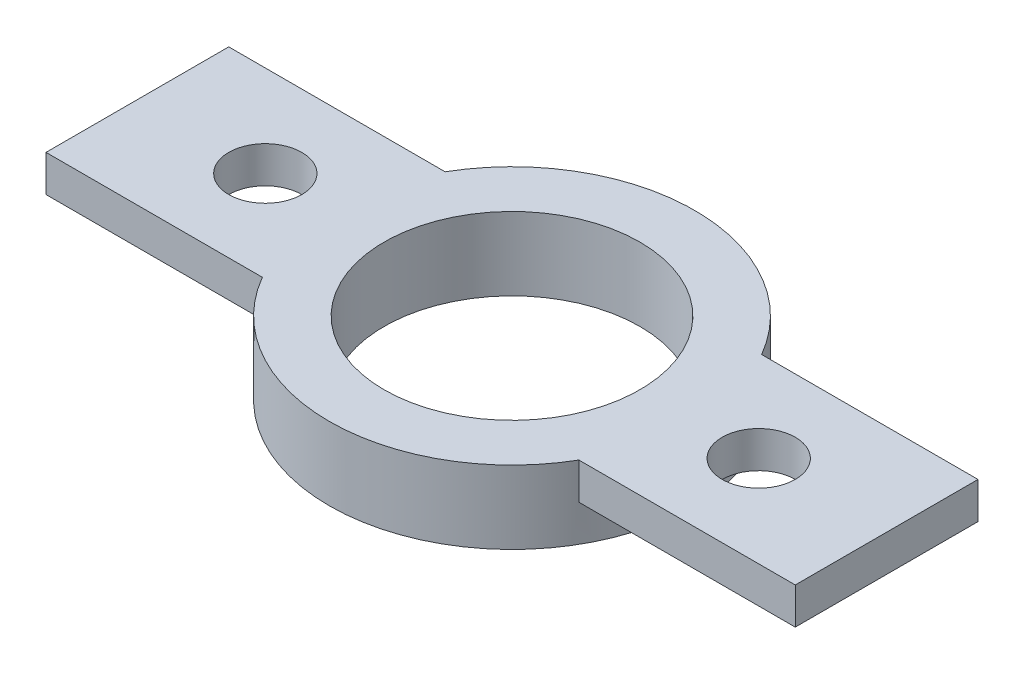
SolidWorks part; units mm, degrees
ref_plane "Front" through (0, 0, 0) normal (0, 0, 1) x (1, 0, 0)
ref_plane "Top" through (0, 0, 0) normal (0, 1, 0) x (1, 0, 0)
ref_plane "Right" through (0, 0, 0) normal (1, 0, 0) x (0, 0, -1)
sketch "Sketch1" plane through (0, 0, 0) normal (0, 1, 0) x (1, 0, 0)
  line L1 (0, 0) -> (35, 0)
  line L2 (0, 0) -> (0, 10)
  line L3 (0, 10) -> (35, 10)
  line L4 (35, 0) -> (35, 10)
  dimension "D1" = 35
  dimension "D2" = 10
extrude "Boss-Extrude1" add sketch "Sketch1" along normal blind 2
sketch "Sketch2" plane through (0, 2, 0) normal (0, 1, 0) x (1, 0, 0)
  line L0 (0, 10) -> (0, 0) construction
  line L2 (0, 0) -> (35, 0) construction
  circle A0 centre (17.5, 5) radius 10
  point P6 (22.496, 10.5283)
  dimension "D1" = 17.5
  dimension "D2" = 5
extrude "Boss-Extrude2" add sketch "Sketch2" against normal blind 4
sketch "Sketch3" plane through (0, 2, 0) normal (0, 1, 0) x (1, 0, 0)
  circle A0 centre (17.5, 5) radius 7
extrude "Cut-Extrude1" cut sketch "Sketch3" against normal blind 2000
sketch "Sketch4" plane through (0, 0, 0) normal (0, -1, 0) x (1, 0, 0)
  line L0 (0, -10) -> (0, 0) construction
  line L1 (35, 0) -> (35, -10) construction
  line L2 (0, 0) -> (8.8397, 0) construction
  line L5 (26.1603, 0) -> (35, 0) construction
  circle A0 centre (4, -5) radius 2
  circle A1 centre (31, -5) radius 2
  point P12 (32.4627, 0)
  point P13 (31.9848, 0)
  dimension "D1" = 4
  dimension "D2" = 4
  dimension "D3" = 5
  dimension "D4" = 5
extrude "Cut-Extrude2" cut sketch "Sketch4" against normal blind 20
sketch "Sketch5" plane through (0, 0, 0) normal (-1, 0, 0) x (0, 0, 1)
  line L1 (0, 2) -> (-10, 2)
  line L2 (0, 2) -> (0, 0)
  line L3 (0, 0) -> (-10, 0)
  line L4 (-10, 2) -> (-10, 0)
extrude "Boss-Extrude3" add sketch "Sketch5" along normal blind 3
sketch "Sketch6" plane through (35, 0, 0) normal (1, 0, 0) x (0, 0, -1)
  line L1 (0, 0) -> (10, 0)
  line L2 (0, 0) -> (0, 2)
  line L3 (0, 2) -> (10, 2)
  line L4 (10, 0) -> (10, 2)
extrude "Boss-Extrude4" add sketch "Sketch6" along normal blind 3
